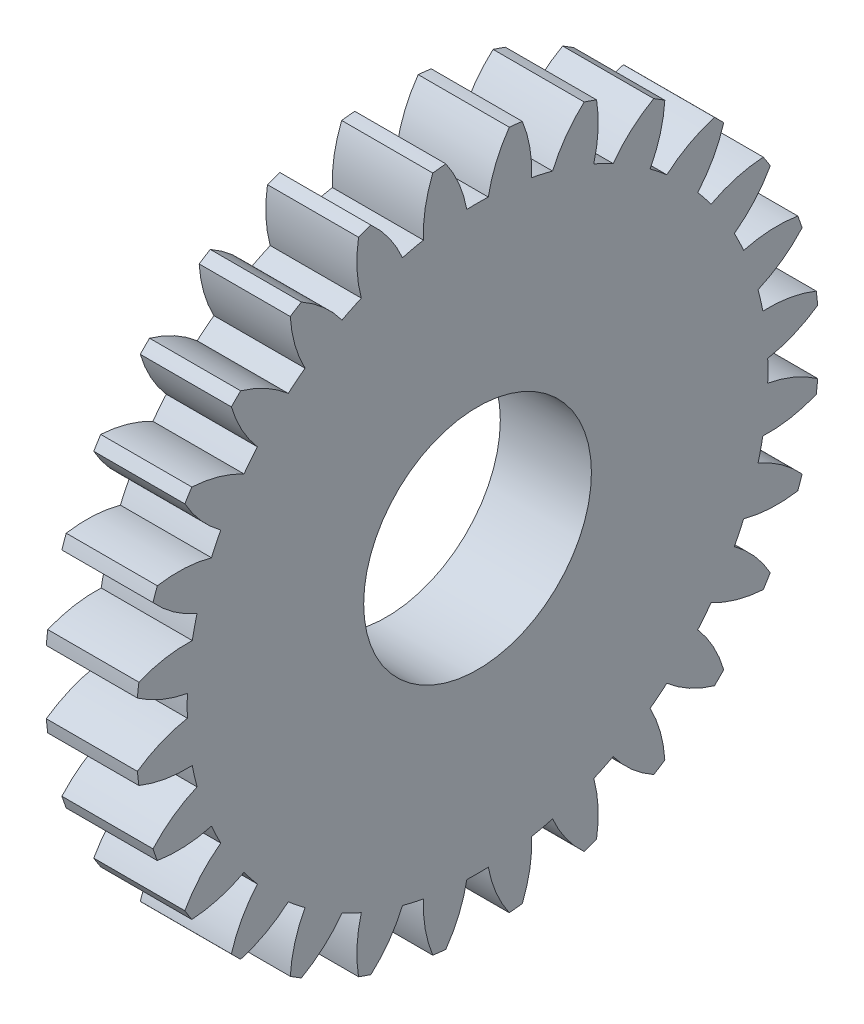
SolidWorks part; units mm, degrees
ref_plane "Plane1" through (0, 0, 0) normal (0, 0, 1) x (1, 0, 0)
ref_plane "Plane2" through (0, 0, 0) normal (0, 1, 0) x (1, 0, 0)
ref_plane "Plane3" through (0, 0, 0) normal (1, 0, 0) x (0, 0, -1)
sketch "HoldingSke" plane through (0, 0, 0) normal (0, 1, 0) x (1, 0, 0)
  line L0 (0, 0) -> (0.8829, -0.4695)
  line L1 (-15, 0) -> (100, 0) construction
  line L2 (0, 0) -> (-2.1039, 2.3779)
  line L3 (0, 0) -> (-11.863, 4.5341)
  line L4 (0, 0) -> (7.6251, 4.0544)
  line L5 (0, 0) -> (-46.8476, -17.4728)
  line L6 (0, 0) -> (-3.3159, -2.2372)
  line L7 (-2.1039, 2.3779) -> (8.6586, 51.2059)
  line L8 (-76.2, 54.61) -> (-74.4, 54.61)
  line L9 (-71.009, 38.7566) -> (-53.1078, 45.2721)
  line L10 (-76.2, 71.12) -> (104.1128, 71.12)
  line L11 (0, 0) -> (-4, 0)
  line L12 (-76.2, 101.6) -> (-76.162, 101.6)
  line L13 (24.9733, 27.94) -> (52.9518, 28.4284)
  line L14 (24.9733, 27.94) -> (24.9743, 27.94)
  line L15 (24.9733, 27.94) -> (100.4006, 29.5858)
  line L16 (-63.627, -1) -> (-12.827, -1)
  circle A0 centre (0, 0) radius 5
  circle A1 centre (0, 0) radius 12.749
  circle A2 centre (0, 0) radius 37.5
  circle A3 centre (0, 0) radius 5
  dimension "MHD" = 25.498
  dimension "Hub_dia" = 75
  dimension "Bore" = 10
  dimension "MBD" = 10
  dimension "Num_teeth" = 28
  dimension "Pitch" = 1
  dimension "Overall_len" = 50
  dimension "Show_teeth" = 28
  dimension "Thickness" = 4
  dimension "OAL" = 50.0001
  dimension "T_dim" = 1.8
  dimension "Ap" = 20
  dimension "H" = 19.05
  dimension "Pitch_radius" = 180.3128
  dimension "Width" = 4
  dimension "Backlash" = 0.038
  dimension "Addendum_fac" = 1
  dimension "Dedendum_fac" = 1.25
  dimension "Clearance_fac" = 0.25
  dimension "Dedendum_add" = 0.001
  dimension "Module" = 1
sketch "BasProSke" plane through (0, 0, 0) normal (0, 1, 0) x (1, 0, 0)
  line L0 (-10, 0) -> (60, 0) construction
  line L1 (0, 0) -> (0, 15)
  line L2 (0, 0) -> (4, 0)
  line L3 (4, 0) -> (4, 15)
  line L4 (4, 15) -> (0, 15)
  dimension "Thickness" = 4
  dimension "Diameter" = 30
revolve "Base-Revolve" add sketch "BasProSke" angle 360 about L0
sketch "TooCutSke" plane through (0, 0, 0) normal (1, 0, 0) x (0, 0, -1)
  line L1 (0, 0) -> (0, 107) construction
  line L2 (0, 0) -> (-0.8515, 13.9741) construction
  line L3 (0, 0) -> (-3.1309, 27.7873) construction
  line L4 (-0.8515, 13.9741) -> (-1.5654, 13.8936) construction
  arc A0 (0.4713, 12.7403) -> (-0.4713, 12.7403) centre (0, 0) ccw
  arc A1 (1.4098, 14.9591) -> (-1.4098, 14.9591) centre (0, 0) ccw
  circle A2 centre (0, 0) radius 14 construction
  circle A3 centre (0, 0) radius 13.1557 construction
  arc A4 (-0.4713, 12.7403) -> (-1.4098, 14.9591) centre (-5.9775, 11.7193) ccw
  arc A5 (1.4098, 14.9591) -> (0.4713, 12.7403) centre (5.9775, 11.7193) ccw
  dimension "Root_dia" = 25.498
  dimension "Overcut_dia" = 30.0508
  dimension "Pitch_dia" = 28
  dimension "Base_dia" = 26.3114
  dimension "Flank_rad" = 5.6
  dimension "Half_ang" = 6.429
  dimension "Half_CT" = 0.7185
extrude "ToothCut" cut sketch "TooCutSke" along normal through all
fillet "Breaks" [suppressed] radius 0.02
fillet "RootFillets" [suppressed] radius 0.251
pattern_circular "TeethCuts" count 28 every 12.857 about axis through (-10, 0, 0) along (1, 0, 0) of "ToothCut", "RootFillets", "Breaks"
sketch "HubNeaOneSke" plane through (0, 0, 0) normal (-1, 0, 0) x (0, 0, 1)
  circle A0 centre (0, 0) radius 12.749
  dimension "Diameter" = 25.498
extrude "HubNearOne" [suppressed] add sketch "HubNeaOneSke" along normal blind 46.0001
sketch "HubNeaBotSke" plane through (0, 0, 0) normal (-1, 0, 0) x (0, 0, 1)
  circle A0 centre (0, 0) radius 12.749
  dimension "Diameter" = 25.498
extrude "HubNearBoth" [suppressed] add sketch "HubNeaBotSke" along normal blind 23
ref_plane "FarPln" through (4, 0, 0) normal (1, 0, 0) x (0, 0, -1)
sketch "HubFarSke" plane through (4, 0, 0) normal (1, 0, 0) x (0, 0, -1)
  circle A0 centre (0, 0) radius 12.749
  dimension "Diameter" = 25.498
extrude "HubFar" [suppressed] add sketch "HubFarSke" along normal blind 23
sketch "BorSke" plane through (0, 0, 0) normal (1, 0, 0) x (0, 0, -1)
  circle A0 centre (0, 0) radius 5
  dimension "Diameter" = 10
extrude "Bore" cut sketch "BorSke" along normal mid plane 100.0001
sketch "KeySke" plane through (0, 0, 0) normal (1, 0, 0) x (0, 0, -1)
  line L0 (-2, 0) -> (-2, 6.8)
  line L1 (-2, 6.8) -> (2, 6.8)
  line L2 (2, 6.8) -> (2, 0)
  line L3 (0, 0) -> (0, 34) construction
  line L4 (-2, 0) -> (2, 0)
  dimension "Width" = 4
  dimension "Offset" = 6.8
extrude "Keyway" [suppressed] cut sketch "KeySke" along normal mid plane 100.0001
pattern_circular "Keyway2" [suppressed] count 2 every 90 about axis through (-10, 0, 0) along (1, 0, 0)
sketch "Sketch1" plane through (4, 0, 0) normal (1, 0, 0) x (0, 0, -1)
  circle A0 centre (0, 0) radius 15
equation "' \"Module@HoldingSke\" = 6.35"
equation "' \"Num_teeth@HoldingSke\" = 12"
equation "' \"Ap@HoldingSke\" =  20"
equation "' \"Ap@HoldingSke\" = 20"
equation "' \"Width@HoldingSke\" = 0.5 * 25.4"
equation "' \"Hub_dia@HoldingSke\"= 1 * 25.4"
equation "' \"Hub_dia@HoldingSke\" = 1 * 25.4"
equation "' \"Overall_len@HoldingSke\" = 1.0 * 25.4"
equation "' \"Bore@HoldingSke\" = 0.75 * 25.4"
equation "' \"T_dim@HoldingSke\" = 0.1 * 25.4"
equation "' \"Width@KeySke\" = 0.25 * 25.4"
equation "' \"Show_teeth@HoldingSke\" = 13"
equation "' \"Backlash@HoldingSke\" = 0.009 * 25.4"
equation "' \"Addendum_fac@HoldingSke\" = 1.0"
equation "' \"Dedendum_fac@HoldingSke\" = 1.25"
equation "' \"Dedendum_add@HoldingSke\" = 0.00005 * 25.4"
equation "' \"Clearance_fac@HoldingSke\" = 0.25"
equation "\"Pitch@HoldingSke\" = 1 / \"Module@HoldingSke\""
equation "\"Overcut_dia@TooCutSke\" = (\"Num_teeth@HoldingSke\" + 2 * \"Addendum_fac@HoldingSke\") / \"Pitch@HoldingSke\" + 0.002 * 25.4"
equation "\"Pitch_dia@TooCutSke\" = \"Num_teeth@HoldingSke\" / \"Pitch@HoldingSke\""
equation "\"Base_dia@TooCutSke\" = \"Num_teeth@HoldingSke\" / \"Pitch@HoldingSke\" * cos((\"Ap@HoldingSke\"  * 3.14159265 / 180))"
equation "\"Root_dia@TooCutSke\" = (\"Num_teeth@HoldingSke\" + 2) / \"Pitch@HoldingSke\" - 2 * (\"Addendum_fac@HoldingSke\" + \"Dedendum_fac@HoldingSke\") / \"Pitch@HoldingSke\" - \"Dedendum_add@HoldingSke\" * 2"
equation "\"Half_ang@TooCutSke\" = 180 / \"Num_teeth@HoldingSke\""
equation "\"Half_CT@TooCutSke\" = \"Num_teeth@HoldingSke\" / \"Pitch@HoldingSke\" * sin((3.14159265 / 2 / \"Num_teeth@HoldingSke\")) / 2 - 7 * \"Backlash@HoldingSke\" / 4"
equation "\"Flank_rad@TooCutSke\" = \"Num_teeth@HoldingSke\" / \"Pitch@HoldingSke\" / 5"
equation "\"Radius@RootFillets\" = \"Clearance_fac@HoldingSke\" / \"Pitch@HoldingSke\" + \"Dedendum_add@HoldingSke\""
equation "\"Break_rad@Breaks\" = 0.02 / \"Pitch@HoldingSke\""
equation "\"Thickness@HoldingSke\" = \"Width@HoldingSke\""
equation "\"OAL@HoldingSke\" = \"Thickness@HoldingSke\""
equation "\"MHD@HoldingSke\" = (\"Num_teeth@HoldingSke\" + 2) / \"Pitch@HoldingSke\" - 2 * (\"Addendum_fac@HoldingSke\" + \"Dedendum_fac@HoldingSke\")  / \"Pitch@HoldingSke\" - \"Dedendum_add@HoldingSke\" * 2"
equation "\"MBD@HoldingSke\" = (\"Num_teeth@HoldingSke\" + 2) / \"Pitch@HoldingSke\" - 2 * (\"Addendum_fac@HoldingSke\" + \"Dedendum_fac@HoldingSke\")  / \"Pitch@HoldingSke\" - \"Dedendum_add@HoldingSke\" * 2 - 0.002 * 25.4"
equation "\"MHD@HoldingSke\" = ((sgn( \"MHD@HoldingSke\" - \"Hub_dia@HoldingSke\" )-1)*( \"MHD@HoldingSke\" - \"Hub_dia@HoldingSke\" ))/-2+ \"Hub_dia@HoldingSke\""
equation "\"MBD@HoldingSke\" = ((sgn( \"MBD@HoldingSke\" - \"Bore@HoldingSke\" )-1)*( \"MBD@HoldingSke\" - \"Bore@HoldingSke\" ))/-2+ \"Bore@HoldingSke\""
equation "\"OAL@HoldingSke\" = ((sgn( \"OAL@HoldingSke\" - \"Overall_len@HoldingSke\" )+1)*( \"OAL@HoldingSke\" - \"Overall_len@HoldingSke\" ))/2 + \"Overall_len@HoldingSke\" + 0.000002 * 25.4"
equation "\"Num_teeth@TeethCuts\" = int( \"Show_teeth@HoldingSke\" ) + 1"
equation "\"Num_teeth@TeethCuts\" = ((sgn( \"Num_teeth@TeethCuts\" - \"Num_teeth@HoldingSke\" )-1)*( \"Num_teeth@TeethCuts\" - \"Num_teeth@HoldingSke\" ))/-2+ \"Num_teeth@HoldingSke\""
equation "\"Num_teeth@TeethCuts\" = ((sgn( \"Num_teeth@TeethCuts\" - 2.0)+1)*( \"Num_teeth@TeethCuts\" - 2.0))/2 +2.0"
equation "\"Angle@TeethCuts\" = 360.0 / \"Num_teeth@HoldingSke\""
equation "\"Diameter@BasProSke\" = (\"Num_teeth@HoldingSke\" + 2 * \"Addendum_fac@HoldingSke\") / \"Pitch@HoldingSke\""
equation "\"Thickness@BasProSke\"  = \"Thickness@HoldingSke\""
equation "' \"Fillet_rad@BasProSke\" =  \"Thickness@HoldingSke\" * 0.05"
equation "' \"Fillet_rad@BasProSke\" = \"Thickness@HoldingSke\" * 0.05"
equation "\"MHD@HoldingSke\" = ((sgn( \"MHD@HoldingSke\" - \"Root_dia@TooCutSke\" )-1)*( \"MHD@HoldingSke\" - \"Root_dia@TooCutSke\" ))/-2+ \"Root_dia@TooCutSke\""
equation "\"Diameter@HubNeaOneSke\" = \"MHD@HoldingSke\""
equation "\"Length@HubNearOne\" = \"OAL@HoldingSke\" - \"Thickness@BasProSke\""
equation "\"Diameter@HubNeaBotSke\" = \"MHD@HoldingSke\""
equation "\"Length@HubNearBoth\" = ( \"OAL@HoldingSke\" - \"Thickness@BasProSke\" ) / 2.0"
equation "\"Thickness@FarPln\" = \"Thickness@BasProSke\""
equation "\"Diameter@HubFarSke\" = \"MHD@HoldingSke\""
equation "\"Length@HubFar\" = ( \"OAL@HoldingSke\" - \"Thickness@BasProSke\" ) / 2.0"
equation "\"Diameter@BorSke\" = \"MBD@HoldingSke\""
equation "\"D1@Bore\" = \"OAL@HoldingSke\" * 2.0"
equation "\"D1@Keyway\" = \"OAL@HoldingSke\" * 2.0"
equation "\"Offset@KeySke\" = \"T_dim@HoldingSke\" + \"MBD@HoldingSke\" / 2.0"
